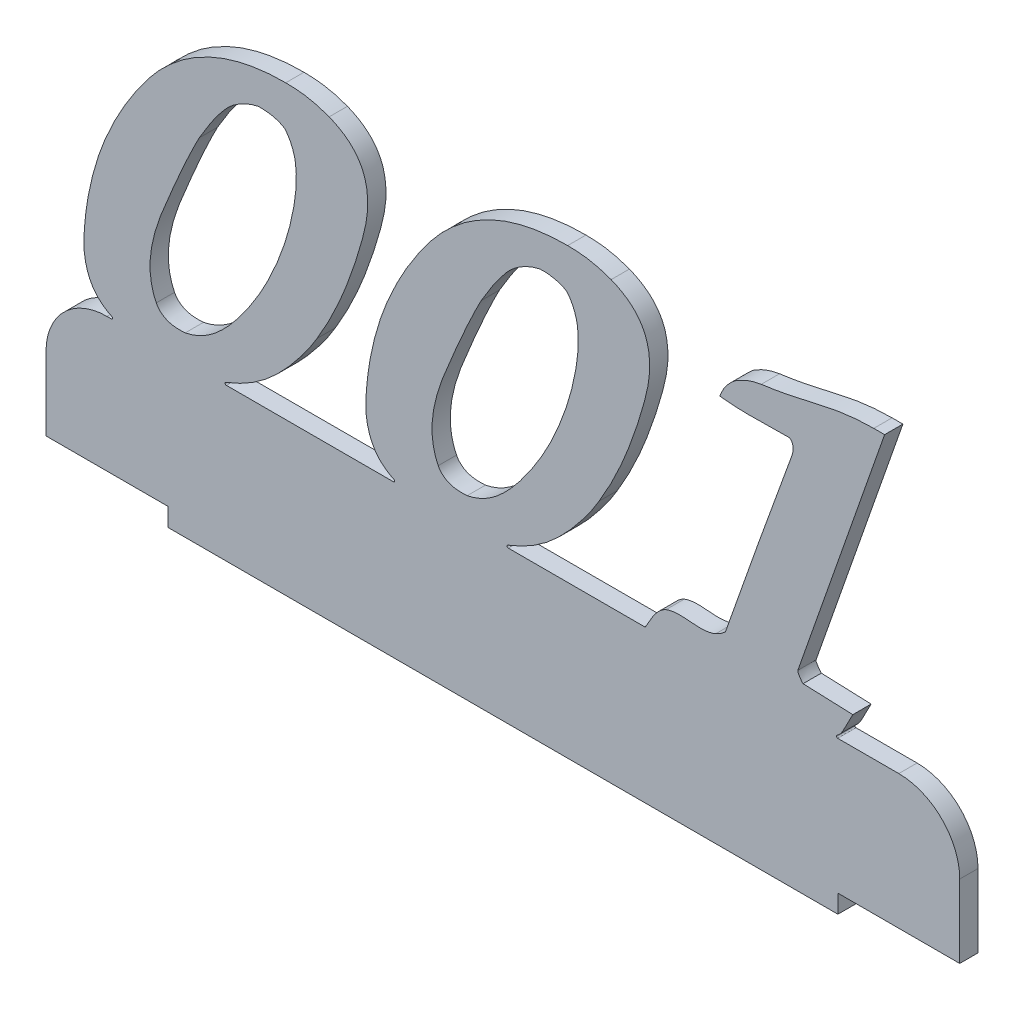
SolidWorks part; units mm, degrees
ref_plane "Front Plane" through (0, 0, 0) normal (0, 0, 1) x (1, 0, 0)
ref_plane "Top Plane" through (0, 0, 0) normal (0, 1, 0) x (1, 0, 0)
ref_plane "Right Plane" through (0, 0, 0) normal (1, 0, 0) x (0, 0, -1)
sketch "Sketch1" plane through (0, 0, 0) normal (0, 0, 1) x (1, 0, 0)
  line L0 (0, 20) -> (150, 20) construction
  line L1 (139.35, 22) -> (150, 22)
  line L2 (0, 22) -> (0, 0)
  line L3 (0, 0) -> (20, 0)
  line L4 (150, 22) -> (150, 0)
  line L5 (0, 22) -> (11.8603, 22)
  line L6 (129.2686, 22) -> (139.35, 22)
  line L7 (137.6715, 69.0225) -> (123.4221, 28.3853)
  line L8 (124.2822, 26.9193) -> (132.4526, 26.6065)
  line L9 (28.4695, 22) -> (58.1465, 22)
  line L10 (74.7557, 22) -> (98.3661, 22)
  line L11 (130, 0) -> (150, 0)
  line L13 (20, 0) -> (20, -3)
  line L14 (20, -3) -> (130, -3)
  line L15 (130, 0) -> (130, -3)
  spline S0 degree 3 poles (39.2157, 63.2758) (38.6144, 63.6853) (37.1492, 64.1915) (35.6114, 64.3188) (34.7982, 64.2727) knots 0 0 0 0 0.469699 1 1 1 1
  spline S1 degree 3 poles (34.7982, 64.2727) (33.6535, 64.032) (32.0355, 63.3545) (30.1471, 61.9769) (27.8392, 59.3988) (26.3055, 56.9473) (25.1618, 54.9685) knots 0 0 0 0 0.25259 0.375811 0.50377 1 1 1 1
  spline S2 degree 3 poles (25.1618, 54.9685) (24.7055, 54.1705) (24.1073, 52.8539) (23.2157, 51.0349) (22.5023, 49.4533) (21.7379, 47.7341) (20.9374, 45.8674) (20.0808, 43.8711) (19.2087, 41.7828) (18.4158, 39.6846) (17.7841, 37.6573) (17.3433, 35.7502) (17.1004, 33.9572) (17.0531, 32.2779) (17.2548, 30.2522) (17.6743, 28.8285) (18.1055, 27.9748) knots 0 0 0 0 0.095871 0.150957 0.21155 0.277044 0.347448 0.42366 0.503899 0.583776 0.657815 0.725493 0.787949 0.846481 0.90051 1 1 1 1
  spline S3 degree 3 poles (18.1055, 27.9748) (18.4639, 27.2318) (19.9634, 26.0245) (21.8763, 26.0079) (22.8553, 26.0788) knots 0 0 0 0 0.446154 1 1 1 1
  spline S4 degree 3 poles (22.8553, 26.0788) (24.3128, 26.3531) (26.4694, 27.3716) (29.0017, 29.5393) (30.9522, 31.6965) (32.819, 34.182) (34.5805, 36.856) (36.1709, 39.6825) (37.5655, 42.6388) (38.7636, 45.6558) (39.7551, 48.6678) (40.4738, 51.6563) (40.9784, 54.5469) (41.148, 57.2487) (40.9461, 60.2792) (40.0713, 62.2678) (39.2157, 63.2758) knots 0 0 0 0 0.099523 0.157976 0.224341 0.295662 0.367825 0.440561 0.514606 0.588508 0.65979 0.72866 0.796042 0.857776 0.911265 1 1 1 1
  spline S5 degree 3 poles (11.8603, 22) (11.4091, 22.146) (10.4843, 22.4885) (9.2383, 23.299) (8.1284, 24.3181) (7.2985, 25.5954) (6.693, 27.0669) (6.1394, 29.4317) (6.209, 31.3514) (6.2994, 32.666) knots 0.509397 0.509397 0.509397 0.509397 0.5623 0.61932 0.674488 0.729675 0.788153 0.851799 1 1 1 1
  spline S6 degree 3 poles (6.2994, 32.666) (6.4663, 34.8941) (6.9555, 38.2196) (8.0849, 42.5564) (9.1477, 45.7658) (10.5023, 48.8991) (12.0403, 52.005) (13.8481, 55.0481) (15.8551, 58.0153) (18.0527, 60.8046) (20.5269, 63.2234) (23.1692, 65.311) (26.0494, 66.9584) (29.0849, 68.3063) (33.5073, 69.5286) (36.986, 69.9133) (39.3525, 69.8825) knots 0 0 0 0 0.122246 0.183381 0.245051 0.307032 0.370011 0.434579 0.500535 0.565958 0.62848 0.689454 0.749684 0.809559 0.870725 1 1 1 1
  spline S7 degree 3 poles (39.3525, 69.8825) (40.6128, 69.8721) (43.0556, 69.7286) (45.3958, 69.0187) (46.487, 68.612) knots 0 0 0 0 0.519885 1 1 1 1
  spline S8 degree 3 poles (46.487, 68.612) (47.7546, 68.0967) (49.5496, 67.1034) (51.2889, 65.1205) (52.1984, 63.447) (52.7137, 61.5421) (52.879, 59.425) (52.6859, 57.0942) (51.9365, 53.7548) (50.658, 49.5884) (48.3568, 43.2848) (46.1599, 38.8586) (44.4933, 36.1062) knots 0 0 0 0 0.111906 0.162582 0.212593 0.265416 0.321766 0.384451 0.454781 0.599581 0.738515 1 1 1 1
  spline S9 degree 3 poles (44.4933, 36.1062) (43.4018, 34.2489) (41.5315, 31.6785) (38.7821, 28.5555) (36.6134, 26.4862) (34.231, 24.6786) (31.5513, 23.1828) (29.5775, 22.3804) (28.5202, 22.0173) (28.4695, 22) knots 0 0 0 0 0.25786 0.380114 0.498337 0.616577 0.737567 0.865048 0.871463 0.871463 0.871463 0.871463
  spline S10 degree 3 poles (85.5019, 63.2758) (84.9006, 63.6853) (83.4353, 64.1915) (81.8975, 64.3188) (81.0844, 64.2727) knots 0 0 0 0 0.469699 1 1 1 1
  spline S11 degree 3 poles (81.0844, 64.2727) (79.9397, 64.032) (78.3216, 63.3545) (76.4332, 61.9769) (74.1253, 59.3988) (72.5916, 56.9473) (71.4479, 54.9685) knots 0 0 0 0 0.25259 0.375811 0.50377 1 1 1 1
  spline S12 degree 3 poles (71.4479, 54.9685) (70.9916, 54.1705) (70.3934, 52.8539) (69.5019, 51.0349) (68.7884, 49.4533) (68.0241, 47.7341) (67.2236, 45.8674) (66.367, 43.8711) (65.4949, 41.7828) (64.7019, 39.6846) (64.0703, 37.6573) (63.6295, 35.7502) (63.3866, 33.9572) (63.3392, 32.2779) (63.5409, 30.2522) (63.9605, 28.8285) (64.3916, 27.9748) knots 0 0 0 0 0.095871 0.150957 0.21155 0.277044 0.347448 0.42366 0.503899 0.583776 0.657815 0.725493 0.787949 0.846481 0.90051 1 1 1 1
  spline S13 degree 3 poles (64.3916, 27.9748) (64.7501, 27.2318) (66.2495, 26.0245) (68.1624, 26.0079) (69.1414, 26.0788) knots 0 0 0 0 0.446154 1 1 1 1
  spline S14 degree 3 poles (69.1414, 26.0788) (70.599, 26.3531) (72.7555, 27.3716) (75.2879, 29.5393) (77.2383, 31.6965) (79.1051, 34.182) (80.8666, 36.856) (82.4571, 39.6825) (83.8516, 42.6388) (85.0498, 45.6558) (86.0413, 48.6678) (86.76, 51.6563) (87.2645, 54.5469) (87.4341, 57.2487) (87.2323, 60.2792) (86.3574, 62.2678) (85.5019, 63.2758) knots 0 0 0 0 0.099523 0.157976 0.224341 0.295662 0.367825 0.440561 0.514606 0.588508 0.65979 0.72866 0.796042 0.857776 0.911265 1 1 1 1
  spline S15 degree 3 poles (58.1465, 22) (57.6952, 22.146) (56.7704, 22.4885) (55.5245, 23.299) (54.4145, 24.3181) (53.5847, 25.5954) (52.9792, 27.0669) (52.4256, 29.4317) (52.4952, 31.3514) (52.5855, 32.666) knots 0.509397 0.509397 0.509397 0.509397 0.5623 0.61932 0.674488 0.729675 0.788153 0.851799 1 1 1 1
  spline S16 degree 3 poles (52.5855, 32.666) (52.7525, 34.8941) (53.2416, 38.2196) (54.371, 42.5564) (55.4339, 45.7658) (56.7885, 48.8991) (58.3265, 52.005) (60.1342, 55.0481) (62.1413, 58.0153) (64.3388, 60.8046) (66.8131, 63.2234) (69.4554, 65.311) (72.3356, 66.9584) (75.3711, 68.3063) (79.7935, 69.5286) (83.2722, 69.9133) (85.6387, 69.8825) knots 0 0 0 0 0.122246 0.183381 0.245051 0.307032 0.370011 0.434579 0.500535 0.565958 0.62848 0.689454 0.749684 0.809559 0.870725 1 1 1 1
  spline S17 degree 3 poles (85.6387, 69.8825) (86.8989, 69.8721) (89.3418, 69.7286) (91.6819, 69.0187) (92.7732, 68.612) knots 0 0 0 0 0.519885 1 1 1 1
  spline S18 degree 3 poles (92.7732, 68.612) (94.0407, 68.0967) (95.8358, 67.1034) (97.5751, 65.1205) (98.4846, 63.447) (98.9999, 61.5421) (99.1652, 59.425) (98.9721, 57.0942) (98.2227, 53.7548) (96.9442, 49.5884) (94.643, 43.2848) (92.4461, 38.8586) (90.7794, 36.1062) knots 0 0 0 0 0.111906 0.162582 0.212593 0.265416 0.321766 0.384451 0.454781 0.599581 0.738515 1 1 1 1
  spline S19 degree 3 poles (90.7794, 36.1062) (89.6879, 34.2489) (87.8176, 31.6785) (85.0683, 28.5555) (82.8996, 26.4862) (80.5172, 24.6786) (77.8374, 23.1828) (75.8637, 22.3804) (74.8064, 22.0173) (74.7557, 22) knots 0 0 0 0 0.25786 0.380114 0.498337 0.616577 0.737567 0.865048 0.871463 0.871463 0.871463 0.871463
  spline S20 degree 3 poles (132.4526, 26.6065) (131.8577, 25.5933) (131.3125, 24.2711) (130.4145, 22.8049) (129.842, 22.3329) (129.4432, 22.0911) (129.2686, 22) knots 0 0 0 0 0.504343 0.619768 0.735364 0.820323 0.820323 0.820323 0.820323
  spline S21 degree 3 poles (98.3661, 22) (98.5428, 22.28) (98.9576, 22.9984) (99.8487, 24.597) (100.8433, 25.7666) (101.7841, 26.1961) knots 0.083264 0.083264 0.083264 0.083264 0.248912 0.498933 1 1 1 1
  spline S22 degree 3 poles (101.7841, 26.1961) (103.1255, 26.7153) (105.8762, 26.4406) (108.6456, 26.2849) (109.9546, 26.8606) knots 0 0 0 0 0.501452 1 1 1 1
  spline S23 degree 2 poles (109.9546, 26.8606) (110.8361, 27.2512) (111.5378, 27.9162) knots 0 0 0 1 1 1
  spline S24 degree 3 poles (111.5378, 27.9162) (113.3201, 32.9513) (116.8451, 43.0741) (120.5342, 53.1383) (122.3666, 58.1937) knots 0 0 0 0 0.498323 1 1 1 1
  spline S25 degree 3 poles (122.3666, 58.1937) (122.5498, 58.6913) (122.845, 59.6578) (122.3924, 60.5692) (122.0343, 60.7739) knots 0 0 0 0 0.581397 1 1 1 1
  spline S26 degree 3 poles (122.0343, 60.7739) (120.1176, 60.8077) (116.3126, 60.6237) (112.4996, 60.7285) (110.6191, 60.9693) knots 0 0 0 0 0.503015 1 1 1 1
  spline S27 degree 3 poles (110.6191, 60.9693) (110.8511, 61.6365) (111.3354, 62.5855) (112.2533, 63.6462) (113.0266, 64.3687) (113.9746, 64.9224) (115.4016, 65.6051) (116.5937, 65.9199) (117.4213, 66.0514) knots 0 0 0 0 0.237267 0.352024 0.469659 0.590381 0.718477 1 1 1 1
  spline S28 degree 3 poles (117.4213, 66.0514) (120.5336, 66.4499) (124.3954, 67.3019) (129.0172, 68.3817) (132.0971, 68.8642) (134.3902, 69.0117) (135.8928, 69.0225) knots 0 0 0 0 0.501478 0.63281 0.759518 1 1 1 1
  spline S29 degree 3 poles (135.8928, 69.0225) (136.1013, 69.0225) (136.6942, 69.0225) (137.2871, 69.0225) (137.6715, 69.0225) knots 0 0 0 0 0.351648 1 1 1 1
  spline S30 degree 3 poles (123.4221, 28.3853) (123.3689, 28.1855) (123.7006, 27.6758) (123.9783, 27.193) (124.2822, 26.9193) knots 0 0 0 0 0.324502 1 1 1 1
  dimension "D1" = 150
  dimension "D2" = 3
  dimension "D3" = 20
  dimension "D4" = 20
  dimension "D5" = 20
extrude "Boss-Extrude1" add sketch "Sketch1" along normal blind 3
fillet "Fillet1" radius 10 2 edges at (0, 22, 1.5) (150, 22, 1.5)
fillet "Fillet2" radius 0.2 6 edges at (11.8603, 22, 1.5) (58.1465, 22, 1.5) (98.3661, 22, 1.5) (129.2686, 22, 1.5) (74.7557, 22, 1.5) (28.4695, 22, 1.5)
